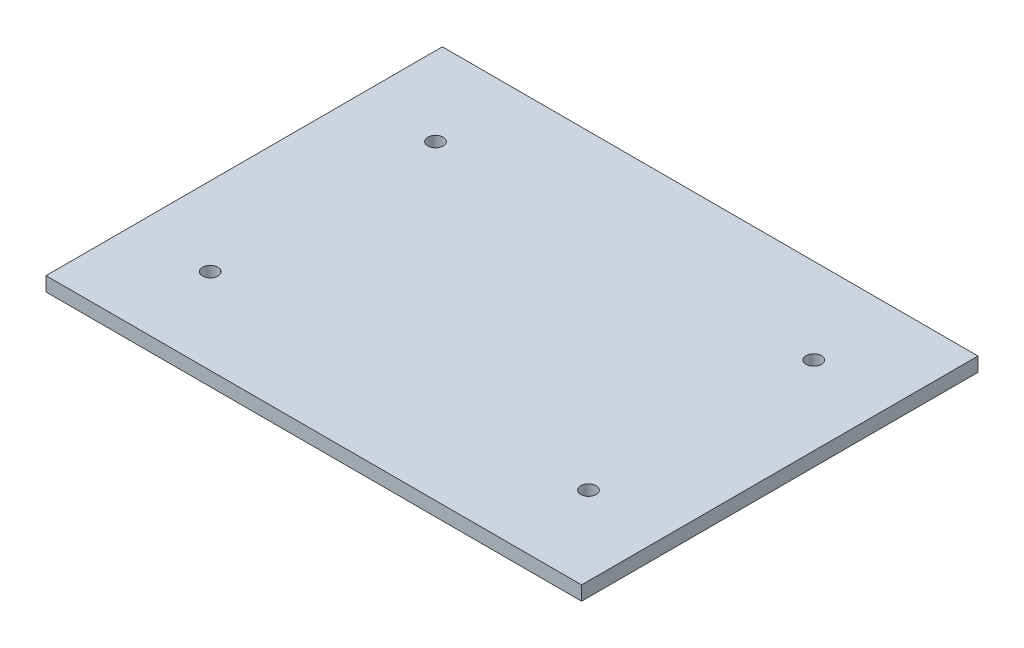
SolidWorks part; units mm, degrees
ref_plane "Front Plane" through (0, 0, 0) normal (0, 0, 1) x (1, 0, 0)
ref_plane "Top Plane" through (0, 0, 0) normal (0, 1, 0) x (1, 0, 0)
ref_plane "Right Plane" through (0, 0, 0) normal (1, 0, 0) x (0, 0, -1)
sketch "Sketch1" plane through (0, 0, 0) normal (0, 1, 0) x (1, 0, 0)
  line L1 (-104.2637, 42.672) -> (122.7363, 42.672)
  line L2 (-104.2637, 42.672) -> (-104.2637, -125.328)
  line L3 (-104.2637, -125.328) -> (122.7363, -125.328)
  line L4 (122.7363, 42.672) -> (122.7363, -125.328)
  dimension "D1" = 227
  dimension "D2" = 168
extrude "Boss-Extrude1" add sketch "Sketch1" along normal blind 6
sketch "Sketch2" plane through (0, 6, 0) normal (0, 1, 0) x (1, 0, 0)
  line L0 (9.2363, -125.328) -> (9.2363, 42.672) construction
  line L1 (-104.2637, -125.328) -> (122.7363, -125.328) construction
  line L2 (122.7363, 42.672) -> (-104.2637, 42.672) construction
  line L3 (122.7363, -41.328) -> (-104.2637, -41.328) construction
  line L4 (122.7363, -125.328) -> (122.7363, 42.672) construction
  line L5 (-104.2637, 42.672) -> (-104.2637, -125.328) construction
  line L7 (-70.9373, 6.4243) -> (89.4099, 6.4243) construction
  line L8 (-70.9373, 6.4243) -> (-70.9373, -89.0803) construction
  line L9 (-70.9373, -89.0803) -> (89.4099, -89.0803) construction
  line L10 (89.4099, 6.4243) -> (89.4099, -89.0803) construction
  line L11 (-70.9373, 6.4243) -> (89.4099, -89.0803) construction
  line L12 (-70.9373, -89.0803) -> (89.4099, 6.4243) construction
  circle A0 centre (89.4099, -89.0803) radius 3.25
  circle A1 centre (-70.9373, -89.0803) radius 3.25
  circle A2 centre (89.4099, 6.4243) radius 3.25
  circle A3 centre (-70.9373, 6.4243) radius 3.25
  point P12 (9.2363, -41.328)
  point P21 (-70.9373, -89.0803)
extrude "Cut-Extrude1" cut sketch "Sketch2" against normal blind 10
